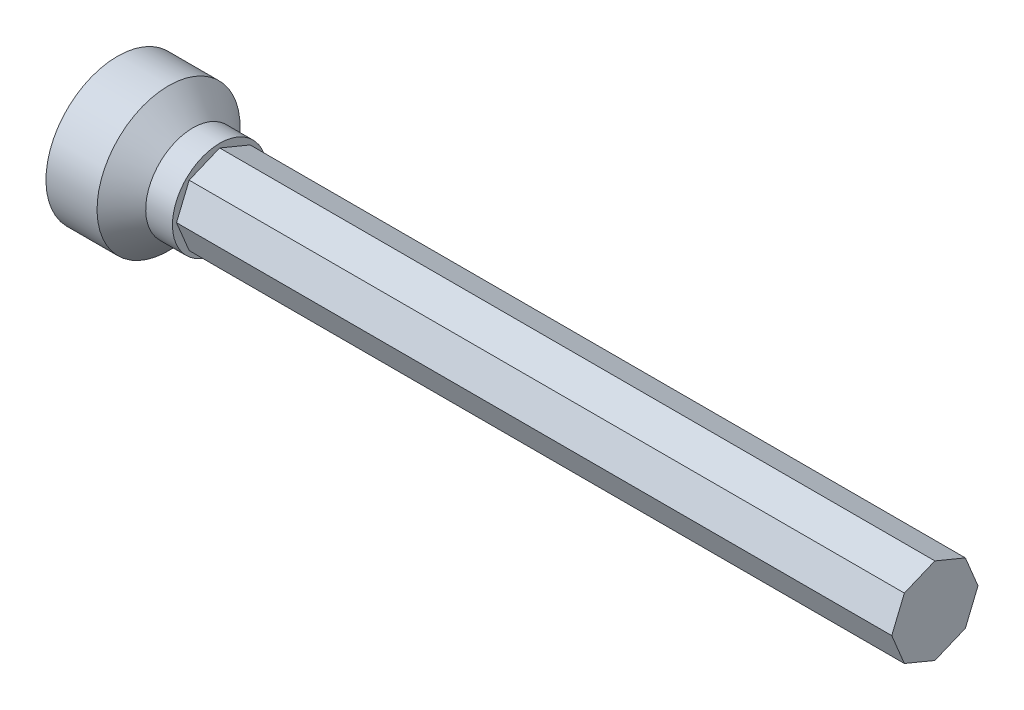
SolidWorks part; units mm, degrees
ref_plane "Front Plane" through (0, 0, 0) normal (0, 0, 1) x (1, 0, 0)
ref_plane "Top Plane" through (0, 0, 0) normal (0, 1, 0) x (1, 0, 0)
ref_plane "Right Plane" through (0, 0, 0) normal (1, 0, 0) x (0, 0, -1)
sketch "Sketch1" plane through (0, 0, 0) normal (1, 0, 0) x (0, 0, -1)
  line L7 (-2.1107, 0) -> (-1.4925, -1.4925)
  line L8 (-1.4925, -1.4925) -> (0, -2.1107)
  line L9 (0, -2.1107) -> (1.4925, -1.4925)
  line L10 (1.4925, -1.4925) -> (2.1107, 0)
  line L11 (2.1107, 0) -> (1.4925, 1.4925)
  line L12 (1.4925, 1.4925) -> (0, 2.1107)
  line L13 (0, 2.1107) -> (-1.4925, 1.4925)
  line L14 (-1.4925, 1.4925) -> (-2.1107, 0)
  circle A1 centre (0, 0) radius 1.95 construction
extrude "Boss-Extrude1" add sketch "Sketch1" along normal blind 35
sketch "Sketch4" plane through (0, 0, 0) normal (0, 0, 1) x (1, 0, 0)
  line L0 (0, 0) -> (-5, 0)
  line L1 (-5, 0) -> (-5, 3.5)
  line L6 (-1.3094, 2.3094) -> (0, 2.3094)
  line L7 (0, 2.3094) -> (0, 0)
  line L8 (-5, 3.5) -> (-2.5, 3.5)
  line L9 (-1.3094, 2.3094) -> (-2.5, 3.5)
  dimension "D1" = 3.5
revolve "Revolve1" add sketch "Sketch4" angle 360 about L0
